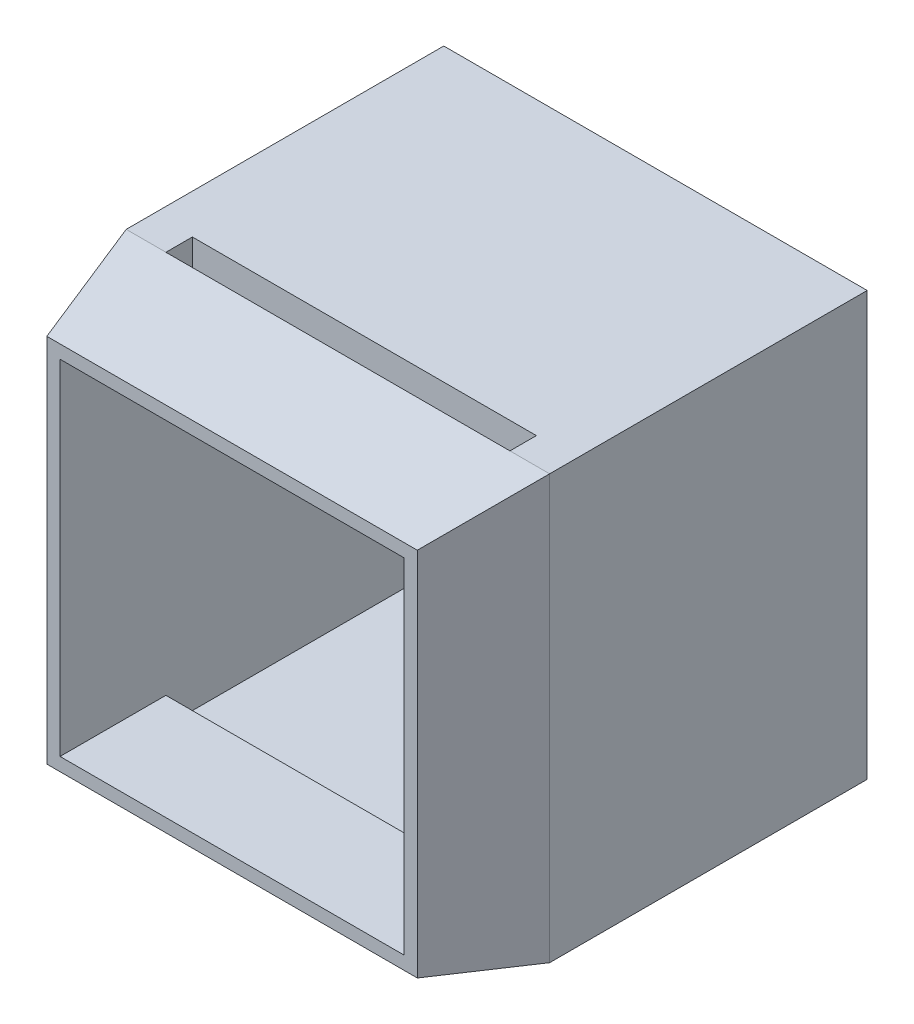
SolidWorks part; units mm, degrees
ref_plane "Front Plane" through (0, 0, 0) normal (0, 0, 1) x (1, 0, 0)
ref_plane "Top Plane" through (0, 0, 0) normal (0, 1, 0) x (1, 0, 0)
ref_plane "Right Plane" through (0, 0, 0) normal (1, 0, 0) x (0, 0, -1)
sketch "Sketch1" plane through (0, 0, 0) normal (0, 0, 1) x (1, 0, 0)
  line L1 (0, 0) -> (406.4, 0)
  line L2 (0, 0) -> (0, 406.4)
  line L3 (0, 406.4) -> (406.4, 406.4)
  line L4 (406.4, 0) -> (406.4, 406.4)
  dimension "D1" = 406.4
  dimension "D2" = 406.4
extrude "Boss-Extrude1" add sketch "Sketch1" along normal blind 304.8
ref_plane "Plane1" through (0, 0, 304.8) normal (0, 0, 1) x (1, 0, 0)
sketch "Sketch3" plane through (0, 0, 304.8) normal (0, 0, 1) x (1, 0, 0)
  line L0 (406.4, 0) -> (406.4, 406.4) construction
  line L1 (0, 0) -> (406.4, 0) construction
  line L2 (0, 406.4) -> (0, 0) construction
  line L3 (406.4, 406.4) -> (0, 406.4) construction
  line L4 (406.4, 0) -> (406.4, 406.4)
  line L5 (0, 0) -> (406.4, 0)
  line L6 (0, 406.4) -> (0, 0)
  line L7 (406.4, 406.4) -> (0, 406.4)
ref_plane "Plane2" through (0, 0, 406.4) normal (0, 0, 1) x (1, 0, 0)
sketch "Sketch2" plane through (0, 0, 406.4) normal (0, 0, 1) x (1, 0, 0)
  line L0 (406.4, 406.4) -> (0, 406.4) construction
  line L1 (25.4, 25.4) -> (381, 25.4)
  line L2 (25.4, 25.4) -> (25.4, 381)
  line L3 (25.4, 381) -> (381, 381)
  line L4 (381, 25.4) -> (381, 381)
  line L5 (0, 406.4) -> (0, 0) construction
  dimension "D1" = 25.4
  dimension "D2" = 25.4
  dimension "D3" = 355.6
  dimension "D4" = 355.6
loft "Loft1" add profiles "Sketch2" section face at (203.2, 203.2, 304.8) section "Sketch2"
sketch "Sketch5" plane through (0, 0, 406.4) normal (0, 0, 1) x (1, 0, 0)
  line L4 (25.4, 381) -> (25.4, 25.4)
  line L5 (25.4, 25.4) -> (381, 25.4)
  line L6 (381, 25.4) -> (381, 381)
  line L7 (381, 381) -> (25.4, 381)
  line L8 (25.4, 381) -> (25.4, 25.4)
  line L9 (25.4, 25.4) -> (381, 25.4)
  line L10 (381, 25.4) -> (381, 381)
  line L11 (381, 381) -> (25.4, 381)
  dimension "D1" = 0
sketch "Sketch6" plane through (0, 0, 406.4) normal (0, 0, 1) x (1, 0, 0)
  line L0 (381, 381) -> (25.4, 381) construction
  line L1 (38.1, 38.1) -> (368.3, 38.1)
  line L2 (38.1, 38.1) -> (38.1, 368.3)
  line L3 (38.1, 368.3) -> (368.3, 368.3)
  line L4 (368.3, 38.1) -> (368.3, 368.3)
  line L5 (25.4, 381) -> (25.4, 25.4) construction
  dimension "D1" = 12.7
  dimension "D2" = 330.2
  dimension "D3" = 12.7
  dimension "D4" = 330.2
extrude "Cut-Extrude2" cut sketch "Sketch6" against normal through all both and the other way through all
sketch "Sketch7" plane through (0, 406.4, 0) normal (0, 1, 0) x (1, 0, 0)
  line L0 (0, -304.8) -> (406.4, -304.8) construction
  line L1 (38.1, -304.8) -> (368.3, -304.8)
  line L2 (38.1, -304.8) -> (38.1, -279.4)
  line L3 (38.1, -279.4) -> (368.3, -279.4)
  line L4 (368.3, -304.8) -> (368.3, -279.4)
  line L5 (0, -304.8) -> (0, 0) construction
  dimension "D1" = 25.4
  dimension "D2" = 330.2
  dimension "D3" = 38.1
extrude "Cut-Extrude3" cut sketch "Sketch7" against normal through all both and the other way through all
sketch "Sketch8" plane through (0, 38.1, 0) normal (0, 1, 0) x (1, 0, 0)
  line L4 (38.1, 0) -> (38.1, -279.4)
  line L5 (38.1, -279.4) -> (368.3, -279.4)
  line L6 (368.3, -279.4) -> (368.3, 0)
  line L7 (368.3, 0) -> (38.1, 0)
  line L8 (38.1, 0) -> (38.1, -279.4)
  line L9 (38.1, -279.4) -> (368.3, -279.4)
  line L10 (368.3, -279.4) -> (368.3, 0)
  line L11 (368.3, 0) -> (38.1, 0)
  dimension "D1" = 0
extrude "Cut-Extrude4" cut sketch "Sketch8" against normal blind 25.4
